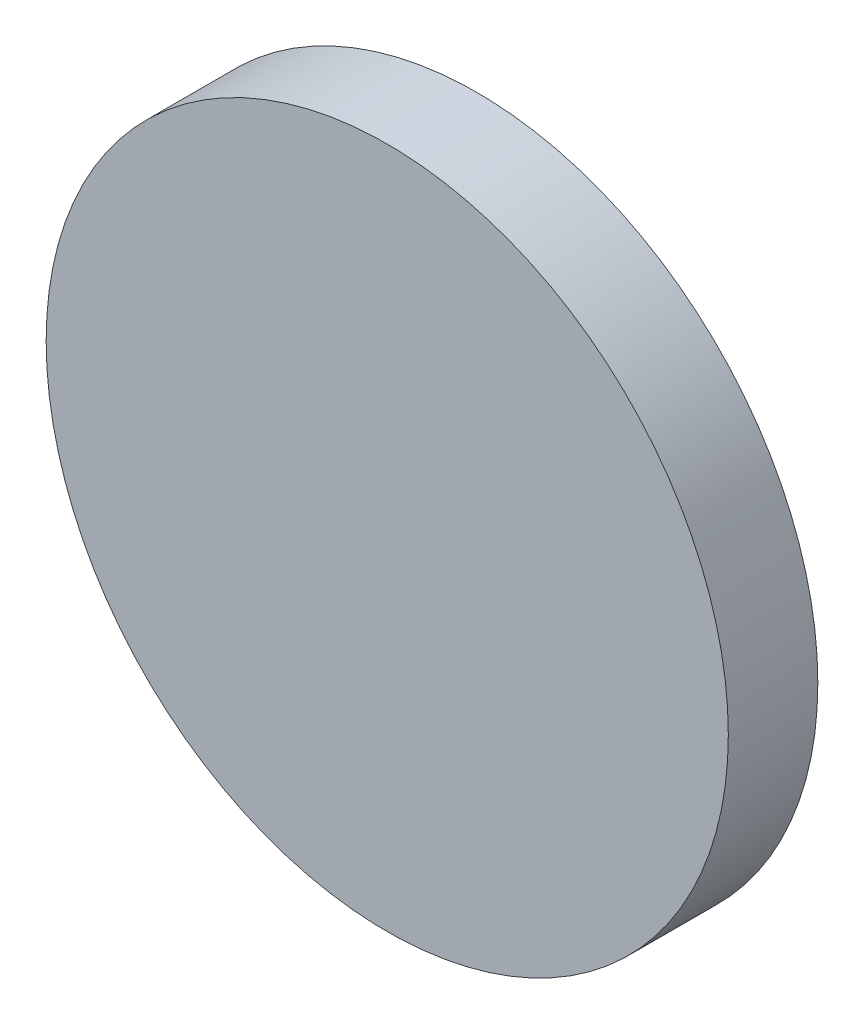
SolidWorks part; units mm, degrees
ref_plane "Front Plane" through (0, 0, 0) normal (0, 0, 1) x (1, 0, 0)
ref_plane "Top Plane" through (0, 0, 0) normal (0, 1, 0) x (1, 0, 0)
ref_plane "Right Plane" through (0, 0, 0) normal (1, 0, 0) x (0, 0, -1)
sketch "Sketch1" plane through (0, 0, 0) normal (0, 0, 1) x (1, 0, 0)
  circle A0 centre (0, 0) radius 38.1
  dimension "D1" = 76.2
extrude "Boss-Extrude1" add sketch "Sketch1" along normal blind 10
